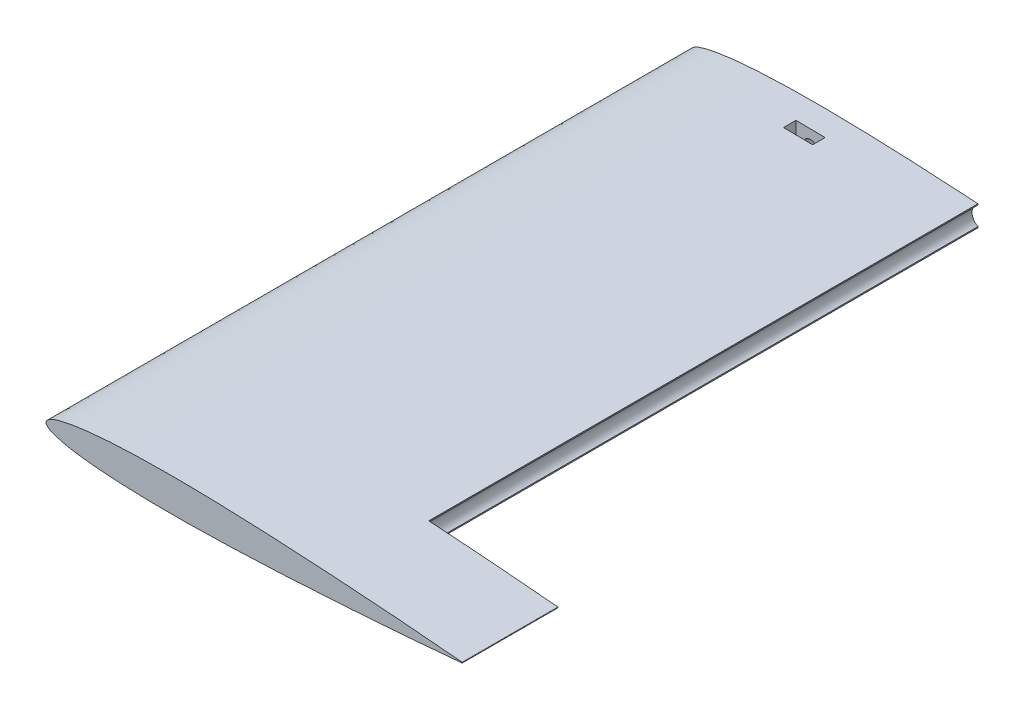
SolidWorks part; units mm, degrees
material "ABS generico"
ref_plane "Piano frontale" through (0, 0, 0) normal (0, 0, 1) x (1, 0, 0)
ref_plane "Piano superiore" through (0, 0, 0) normal (0, 1, 0) x (1, 0, 0)
ref_plane "Piano destro" through (0, 0, 0) normal (1, 0, 0) x (0, 0, -1)
curve "Curva1"
  spline degree 3 poles (100, 0.084, 0) (98.3335, 0.2367, 0) (95.0012, 0.5422, 0) (88.3356, 1.1109, 0) (80.0033, 1.7636, 0) (70.003, 2.4579, 0) (60.0031, 3.0617, 0) (50.003, 3.5521, 0) (40.0026, 3.9029, 0) (31.667, 4.0253, 0) (24.9992, 3.9769, 0) (19.9978, 3.845, 0) (14.9934, 3.5925, 0) (10.8272, 3.2377, 0) (7.4891, 2.814, 0) (4.9936, 2.4037, 0) (2.8496, 1.8679, 0) (1.1654, 1.321, 0) (-0.6646, 0, 0) (1.1654, -1.321, 0) (2.8496, -1.8679, 0) (4.9936, -2.4037, 0) (7.4891, -2.814, 0) (10.8272, -3.2377, 0) (14.9934, -3.5925, 0) (19.9978, -3.845, 0) (24.9992, -3.9769, 0) (31.667, -4.0253, 0) (40.0026, -3.9029, 0) (50.003, -3.5521, 0) (60.0031, -3.0617, 0) (70.003, -2.4579, 0) (80.0033, -1.7636, 0) (88.3356, -1.1109, 0) (95.0012, -0.5422, 0) (98.3335, -0.2367, 0) (100, -0.084, 0) knots 0 0 0 0 0.024876 0.049742 0.099443 0.149112 0.198751 0.248359 0.297937 0.347491 0.372267 0.397051 0.421859 0.446731 0.45922 0.471791 0.48456 0.491195 0.5 0.508805 0.51544 0.528209 0.54078 0.553269 0.578141 0.602949 0.627733 0.652509 0.702063 0.751641 0.801249 0.850888 0.900557 0.950258 0.975124 1 1 1 1
sketch "Schizzo1" plane through (0, 0, 0) normal (0, 0, 1) x (1, 0, 0)
  line L0 (70, 2.443) -> (70, -2.443) construction
  arc A1 (70, -2.443) -> (70, 2.443) centre (70, 0) cw
  spline S0 degree 3 poles (905.2539, 3897.2705) (397.5402, -70.8596) (246.6176, -12.3941) (88.3356, 1.1109) (80.0033, 1.7636) (70.003, 2.4579) (60.0031, 3.0617) (50.003, 3.5521) (40.0026, 3.9029) (31.667, 4.0253) (24.9992, 3.9769) (19.9978, 3.845) (14.9934, 3.5925) (10.8272, 3.2377) (7.4891, 2.814) (4.9936, 2.4037) (2.8496, 1.8679) (1.1654, 1.321) (-0.6646, 0) (1.1654, -1.321) (2.8496, -1.8679) (4.9936, -2.4037) (7.4891, -2.814) (10.8272, -3.2377) (14.9934, -3.5925) (19.9978, -3.845) (24.9992, -3.9769) (31.667, -4.0253) (40.0026, -3.9029) (50.003, -3.5521) (60.0031, -3.0617) (70.003, -2.4579) (80.0033, -1.7636) (88.3356, -1.1109) (246.6156, 12.3939) (397.5363, 70.8581) (905.2338, -3897.1134) knots -2.261938 -2.261938 -2.261938 -2.261938 0.024876 0.049742 0.099443 0.149112 0.198751 0.248359 0.297937 0.347491 0.372267 0.397051 0.421859 0.446731 0.45922 0.471791 0.48456 0.491195 0.5 0.508805 0.51544 0.528209 0.54078 0.553269 0.578141 0.602949 0.627733 0.652509 0.702063 0.751641 0.801249 0.850888 0.900557 0.950258 0.975124 3.261907 3.261907 3.261907 3.261907 only from (100, 0.084) to (100, -0.084) construction
  spline S1 degree 3 poles (70, 2.443) (66.6677, 2.6593) (60.0031, 3.0617) (50.003, 3.5521) (40.0026, 3.9029) (31.667, 4.0253) (24.9992, 3.9769) (19.9978, 3.845) (14.9934, 3.5925) (10.8272, 3.2377) (7.4891, 2.814) (4.9936, 2.4037) (2.8496, 1.8679) (1.1654, 1.321) (-0.6646, 0) (1.1654, -1.321) (2.8496, -1.8679) (4.9936, -2.4037) (7.4891, -2.814) (10.8272, -3.2377) (14.9934, -3.5925) (19.9978, -3.845) (24.9992, -3.9769) (31.667, -4.0253) (40.0026, -3.9029) (50.003, -3.5521) (60.0031, -3.0617) (66.6677, -2.6593) (70, -2.443) knots 0.149112 0.149112 0.149112 0.149112 0.198751 0.248359 0.297937 0.347491 0.372267 0.397051 0.421859 0.446731 0.45922 0.471791 0.48456 0.491195 0.5 0.508805 0.51544 0.528209 0.54078 0.553269 0.578141 0.602949 0.627733 0.652509 0.702063 0.751641 0.801249 0.850888 0.850888 0.850888 0.850888
  dimension "D1" = 4.886
extrude "CorpoFoam" add sketch "Schizzo1" along normal blind 132
sketch "Schizzo7" plane through (0, 0, 132) normal (0, 0, 1) x (1, 0, 0)
  arc A0 (100, 0.084) -> (100, -0.084) centre (100, 0) cw
  spline S0 degree 3 poles (774.5938, 2905.893) (370.1816, -60.6448) (232.5901, -11.1972) (88.3356, 1.1109) (80.0033, 1.7636) (70.003, 2.4579) (60.0031, 3.0617) (50.003, 3.5521) (40.0026, 3.9029) (31.667, 4.0253) (24.9992, 3.9769) (19.9978, 3.845) (14.9934, 3.5925) (10.8272, 3.2377) (7.4891, 2.814) (4.9936, 2.4037) (2.8496, 1.8679) (1.1654, 1.321) (-0.6646, 0) (1.1654, -1.321) (2.8496, -1.8679) (4.9936, -2.4037) (7.4891, -2.814) (10.8272, -3.2377) (14.9934, -3.5925) (19.9978, -3.845) (24.9992, -3.9769) (31.667, -4.0253) (40.0026, -3.9029) (50.003, -3.5521) (60.0031, -3.0617) (70.003, -2.4579) (80.0033, -1.7636) (88.3356, -1.1109) (232.5893, 11.1971) (370.1799, 60.6442) (774.5865, -2905.8392) knots -2.052665 -2.052665 -2.052665 -2.052665 0.024876 0.049742 0.099443 0.149112 0.198751 0.248359 0.297937 0.347491 0.372267 0.397051 0.421859 0.446731 0.45922 0.471791 0.48456 0.491195 0.5 0.508805 0.51544 0.528209 0.54078 0.553269 0.578141 0.602949 0.627733 0.652509 0.702063 0.751641 0.801249 0.850888 0.900557 0.950258 0.975124 3.052652 3.052652 3.052652 3.052652 only from (100, 0.084) to (100, -0.084) construction
  spline S1 degree 3 poles (100, 0.084) (98.3335, 0.2367) (95.0012, 0.5422) (88.3356, 1.1109) (80.0033, 1.7636) (70.003, 2.4579) (60.0031, 3.0617) (50.003, 3.5521) (40.0026, 3.9029) (31.667, 4.0253) (24.9992, 3.9769) (19.9978, 3.845) (14.9934, 3.5925) (10.8272, 3.2377) (7.4891, 2.814) (4.9936, 2.4037) (2.8496, 1.8679) (1.1654, 1.321) (-0.6646, 0) (1.1654, -1.321) (2.8496, -1.8679) (4.9936, -2.4037) (7.4891, -2.814) (10.8272, -3.2377) (14.9934, -3.5925) (19.9978, -3.845) (24.9992, -3.9769) (31.667, -4.0253) (40.0026, -3.9029) (50.003, -3.5521) (60.0031, -3.0617) (70.003, -2.4579) (80.0033, -1.7636) (88.3356, -1.1109) (95.0012, -0.5422) (98.3335, -0.2367) (100, -0.084) knots 0 0 0 0 0.024876 0.049742 0.099443 0.149112 0.198751 0.248359 0.297937 0.347491 0.372267 0.397051 0.421859 0.446731 0.45922 0.471791 0.48456 0.491195 0.5 0.508805 0.51544 0.528209 0.54078 0.553269 0.578141 0.602949 0.627733 0.652509 0.702063 0.751641 0.801249 0.850888 0.900557 0.950258 0.975124 1 1 1 1
extrude "FoamLaterale" add sketch "Schizzo7" along normal blind 23
sketch "Schizzo2" plane through (0, 0, 155) normal (0, 0, 1) x (1, 0, 0)
  line L0 (25, 0) -> (0, 0) construction
  circle A0 centre (25, 0) radius 3
  dimension "D1" = 6
  dimension "D2" = 25
extrude "ForoLongherone" cut sketch "Schizzo2" against normal through all
sketch "Schizzo6" plane through (0, 0, 0) normal (0, 0, -1) x (-1, 0, 0)
  line L0 (-72, 0) -> (-70, 0) construction
  line L1 (-72, 2.5074) -> (-69, 2.5074)
  line L2 (-72, 2.5074) -> (-72, -2.5074)
  line L3 (-72, -2.5074) -> (-69, -2.5074)
  line L4 (-69, 2.5074) -> (-69, -2.5074)
  spline S0 degree 3 poles (-70, 2.443) (-66.6677, 2.6593) (-60.0031, 3.0617) (-50.003, 3.5521) (-40.0026, 3.9029) (-31.667, 4.0253) (-24.9992, 3.9769) (-19.9978, 3.845) (-14.9934, 3.5925) (-10.8272, 3.2377) (-7.4891, 2.814) (-4.9936, 2.4037) (-2.8496, 1.8679) (-1.1654, 1.321) (0.6646, 0) (-1.1654, -1.321) (-2.8496, -1.8679) (-4.9936, -2.4037) (-7.4891, -2.814) (-10.8272, -3.2377) (-14.9934, -3.5925) (-19.9978, -3.845) (-24.9992, -3.9769) (-31.667, -4.0253) (-40.0026, -3.9029) (-50.003, -3.5521) (-60.0031, -3.0617) (-66.6677, -2.6593) (-70, -2.443) knots 0.149112 0.149112 0.149112 0.149112 0.198751 0.248359 0.297937 0.347491 0.372267 0.397051 0.421859 0.446731 0.45922 0.471791 0.48456 0.491195 0.5 0.508805 0.51544 0.528209 0.54078 0.553269 0.578141 0.602949 0.627733 0.652509 0.702063 0.751641 0.801249 0.850888 0.850888 0.850888 0.850888 construction
  dimension "D1" = 3
  dimension "D2" = 1
extrude "SmussoPosteriore" cut sketch "Schizzo6" against normal up to surface (132 mm away) up to face at (84.4102, -0.5898, 132)
sketch "Schizzo8" plane through (0, 0, 155) normal (0, 0, 1) x (1, 0, 0)
  line L0 (69, 1.5) -> (73, 1.5) construction
  line L9 (73, -1.5) -> (69, -1.5) construction
  arc A1 (100, -0.084) -> (100, 0.084) centre (100, 0) ccw construction
  arc A2 (69, 1.5) -> (69, -1.5) centre (71, 0) ccw construction
  arc A3 (73, -1.5) -> (73, 1.5) centre (71, 0) ccw construction
  circle A4 centre (71, 0) radius 1.5
  point P6 (100.084, 0)
  dimension "D1" = 3
  dimension "D3" = 5
  dimension "D2" = 29
  dimension "D4" = 4
extrude "ForoPerno" cut sketch "Schizzo8" against normal through all
sketch "Schizzo9" plane through (0, 0, 155) normal (0, 0, 1) x (1, 0, 0)
  circle A0 centre (25, 0) radius 3 construction
  circle A1 centre (25, 0) radius 3
  circle A2 centre (71, 0) radius 1.5 construction
  circle A3 centre (71, 0) radius 1.5
extrude "ChiusuraForiTerminali" add sketch "Schizzo9" against normal blind 5
sketch "Schizzo10" plane through (0, 0, 0) normal (0, 0, -1) x (-1, 0, 0)
  line L0 (-34.75, 0) -> (-25, 0) construction
  line L1 (-28, 3.995) -> (-28, -3.995) construction
  line L2 (-33, 3.9881) -> (-33, -3.9881) construction
  circle A0 centre (-34.75, 0) radius 1.75
  circle A1 centre (-25, 0) radius 3 construction
  spline S0 degree 3 poles (-69, 2.5074) (-66.0008, 2.6994) (-59.6695, 3.0781) (-50.003, 3.5521) (-40.0026, 3.9029) (-31.667, 4.0253) (-24.9992, 3.9769) (-19.9978, 3.845) (-14.9934, 3.5925) (-10.8272, 3.2377) (-7.4891, 2.814) (-4.9936, 2.4037) (-2.8496, 1.8679) (-1.1654, 1.321) (0.6646, 0) (-1.1654, -1.321) (-2.8496, -1.8679) (-4.9936, -2.4037) (-7.4891, -2.814) (-10.8272, -3.2377) (-14.9934, -3.5925) (-19.9978, -3.845) (-24.9992, -3.9769) (-31.667, -4.0253) (-40.0026, -3.9029) (-50.003, -3.5521) (-59.6695, -3.0781) (-66.0008, -2.6994) (-69, -2.5074) knots 0.154077 0.154077 0.154077 0.154077 0.198751 0.248359 0.297937 0.347491 0.372267 0.397051 0.421859 0.446731 0.45922 0.471791 0.48456 0.491195 0.5 0.508805 0.51544 0.528209 0.54078 0.553269 0.578141 0.602949 0.627733 0.652509 0.702063 0.751641 0.801249 0.845923 0.845923 0.845923 0.845923 construction
  dimension "D1" = 3.5
  dimension "D2" = 5
extrude "ForoVite" cut sketch "Schizzo10" against normal blind 13
ref_plane "PianoDado" through (0, 0, 6) normal (0, 0, -1) x (-1, 0, 0)
sketch "Schizzo11" plane through (0, 0, 6) normal (0, 0, 1) x (1, 0, 0)
  line L0 (31.25, 0) -> (31.25, 7.7052)
  line L1 (31.25, 0) -> (33, -3.0311) construction
  line L2 (33, -3.0311) -> (36.5, -3.0311) construction
  line L3 (36.5, -3.0311) -> (38.25, 0) construction
  line L4 (38.25, 0) -> (36.5, 3.0311) construction
  line L5 (36.5, 3.0311) -> (33, 3.0311) construction
  line L6 (33, 3.0311) -> (31.25, 0) construction
  line L7 (31.25, 7.7052) -> (38.25, 7.7052)
  line L8 (38.25, 7.7052) -> (38.25, 0)
  line L12 (31.25, 0) -> (33, -3.0311)
  line L13 (33, -3.0311) -> (36.5, -3.0311)
  line L14 (36.5, -3.0311) -> (38.25, 0)
  circle A0 centre (34.75, 0) radius 3.0311 construction
  dimension "D1" = 3.5
  dimension "D2" = 7.7052
extrude "TaglioDado" cut sketch "Schizzo11" along normal blind 3
